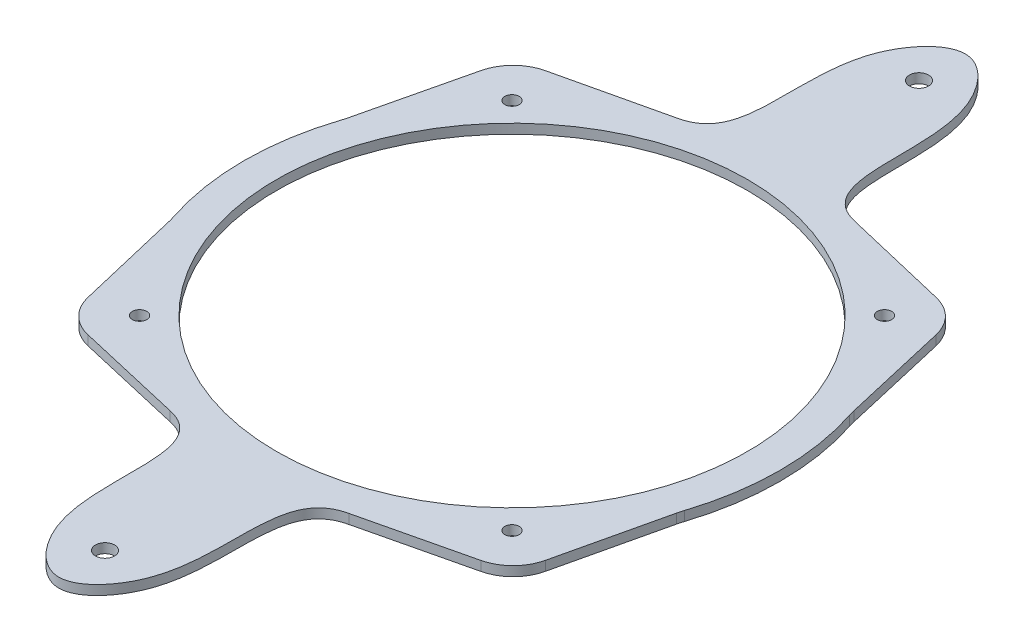
SolidWorks part; units mm, degrees
material "6061-T6 (SS)"
ref_plane "Front Plane" through (0, 0, 0) normal (0, 0, 1) x (1, 0, 0)
ref_plane "Top Plane" through (0, 0, 0) normal (0, 1, 0) x (1, 0, 0)
ref_plane "Right Plane" through (0, 0, 0) normal (1, 0, 0) x (0, 0, -1)
sketch "Sketch1" plane through (0, 0, 0) normal (0, 1, 0) x (1, 0, 0)
  line L0 (49.872, -261.8935) -> (473.872, -261.8935) construction
  line L1 (17.8971, 48.9297) -> (40.1493, 43.6512) construction
  line L2 (43.8664, 39.9141) -> (49.0252, 17.6338) construction
  line L3 (48.9297, -17.8971) -> (43.6512, -40.1493) construction
  line L4 (39.9141, -43.8664) -> (17.6338, -49.0252) construction
  line L5 (-17.8971, -48.9297) -> (-40.1493, -43.6512) construction
  line L6 (-43.8664, -39.9141) -> (-49.0252, -17.6338) construction
  line L7 (-48.9297, 17.8971) -> (-43.6512, 40.1493) construction
  line L8 (-39.9141, 43.8664) -> (-17.6338, 49.0252) construction
  line L9 (-40.8164, 47.7633) -> (-18.5361, 52.9221)
  line L10 (18.8203, 52.8217) -> (41.0725, 47.5432)
  line L11 (47.7633, 40.8164) -> (52.9221, 18.5361)
  line L12 (-38.8907, 38.8907) -> (38.8907, 38.8907) construction
  line L13 (-38.8907, 38.8907) -> (-38.8907, -38.8907) construction
  line L14 (-38.8907, -38.8907) -> (38.8907, -38.8907) construction
  line L15 (38.8907, 38.8907) -> (38.8907, -38.8907) construction
  line L20 (-52.8217, 18.8203) -> (-47.5432, 41.0725)
  line L21 (0, 38.8907) -> (0, -38.8907) construction
  line L22 (-38.8907, 0) -> (38.8907, 0) construction
  line L23 (0, 38.8907) -> (0, 94.647) construction
  line L24 (-9.2568, 85.9478) -> (0, 85.9478) construction
  line L25 (0, 85.9478) -> (9.2568, 85.9478) construction
  line L26 (-38.8907, 0) -> (-56, 0) construction
  line L27 (38.8907, 0) -> (56, 0) construction
  line L28 (-47.7633, -40.8164) -> (-52.9221, -18.5361) construction
  line L29 (-18.8203, -52.8217) -> (-41.0725, -47.5432) construction
  line L30 (40.8164, -47.7633) -> (18.5361, -52.9221) construction
  line L31 (52.8217, -18.8203) -> (47.5432, -41.0725) construction
  line L32 (-52.8217, -18.8203) -> (-47.5432, -41.0725)
  line L33 (-40.8164, -47.7633) -> (-18.5361, -52.9221)
  line L34 (18.8203, -52.8217) -> (41.0725, -47.5432)
  line L35 (47.7633, -40.8164) -> (52.9221, -18.5361)
  line L36 (0, -38.8907) -> (0, -94.647) construction
  arc A1 (-17.6338, 49.0252) -> (-15.9939, 49.4792) centre (-22.1454, 68.5097) ccw construction
  arc A2 (0.1397, 51.9998) -> (-15.9939, 49.4792) centre (0, 0) ccw construction
  arc A3 (16.2596, 49.3926) -> (0.1397, 51.9998) centre (0, 0) ccw construction
  arc A4 (16.2596, 49.3926) -> (17.8971, 48.9297) centre (22.5132, 68.3897) ccw construction
  arc A5 (43.8664, 39.9141) -> (40.1493, 43.6512) centre (38.9952, 38.7862) ccw construction
  arc A6 (49.0252, 17.6338) -> (49.4792, 15.9939) centre (68.5097, 22.1454) ccw construction
  arc A7 (49.3926, -16.2596) -> (49.4792, 15.9939) centre (0, 0) ccw construction
  arc A8 (49.3926, -16.2596) -> (48.9297, -17.8971) centre (68.3897, -22.5132) ccw construction
  arc A9 (39.9141, -43.8664) -> (43.6512, -40.1493) centre (38.7862, -38.9952) ccw construction
  arc A10 (17.6338, -49.0252) -> (15.9939, -49.4792) centre (22.1454, -68.5097) ccw construction
  arc A11 (-16.2596, -49.3926) -> (15.9939, -49.4792) centre (0, 0) ccw construction
  arc A12 (-16.2596, -49.3926) -> (-17.8971, -48.9297) centre (-22.5132, -68.3897) ccw construction
  arc A13 (-43.8664, -39.9141) -> (-40.1493, -43.6512) centre (-38.9952, -38.7862) ccw construction
  arc A14 (-49.0252, -17.6338) -> (-49.4792, -15.9939) centre (-68.5097, -22.1454) ccw construction
  arc A15 (-49.3926, 16.2596) -> (-49.4792, -15.9939) centre (0, 0) ccw construction
  arc A16 (-49.3926, 16.2596) -> (-48.9297, 17.8971) centre (-68.3897, 22.5132) ccw construction
  arc A17 (-39.9141, 43.8664) -> (-43.6512, 40.1493) centre (-38.7862, 38.9952) ccw construction
  circle A18 centre (-38.8907, 38.8907) radius 1.5
  circle A19 centre (38.8907, 38.8907) radius 1.5
  circle A20 centre (38.8907, -38.8907) radius 1.5
  circle A21 centre (-38.8907, -38.8907) radius 1.5
  arc A30 (47.7633, 40.8164) -> (41.0725, 47.5432) centre (38.9952, 38.7862) ccw
  arc A31 (52.9221, 18.5361) -> (53.2853, 17.2242) centre (68.5097, 22.1454) ccw
  arc A32 (53.2853, -17.2242) -> (53.2853, 17.2242) centre (0, 0) ccw
  arc A40 (-53.192, 17.5103) -> (-53.192, -17.5103) centre (0, 0) ccw
  arc A41 (-53.192, 17.5103) -> (-52.8217, 18.8203) centre (-68.3897, 22.5132) ccw
  arc A42 (-40.8164, 47.7633) -> (-47.5432, 41.0725) centre (-38.7862, 38.9952) ccw
  circle A43 centre (0, 0) radius 49.2
  arc A44 (-53.192, 17.5103) -> (-53.2853, -17.2242) centre (0, 0) ccw construction
  arc A45 (-52.9221, -18.5361) -> (-53.2853, -17.2242) centre (-68.5097, -22.1454) ccw construction
  arc A46 (-47.7633, -40.8164) -> (-41.0725, -47.5432) centre (-38.9952, -38.7862) ccw construction
  arc A47 (-17.5103, -53.192) -> (17.2242, -53.2853) centre (0, 0) ccw construction
  arc A48 (-17.5103, -53.192) -> (-18.8203, -52.8217) centre (-22.5132, -68.3897) ccw construction
  arc A49 (18.5361, -52.9221) -> (17.2242, -53.2853) centre (22.1454, -68.5097) ccw construction
  arc A50 (40.8164, -47.7633) -> (47.5432, -41.0725) centre (38.7862, -38.9952) ccw construction
  arc A51 (53.192, -17.5103) -> (52.8217, -18.8203) centre (68.3897, -22.5132) ccw construction
  arc A52 (53.192, -17.5103) -> (53.2853, 17.2242) centre (0, 0) ccw construction
  arc A53 (0.1505, 55.9998) -> (-17.2242, 53.2853) centre (0, 0) ccw construction
  arc A54 (17.5103, 53.192) -> (0.1505, 55.9998) centre (0, 0) ccw construction
  arc A55 (-18.5361, 52.9221) -> (-17.2242, 53.2853) centre (-22.1454, 68.5097) ccw construction
  arc A56 (17.5103, 53.192) -> (18.8203, 52.8217) centre (22.5132, 68.3897) ccw construction
  arc A57 (-53.192, -17.5103) -> (-52.8217, -18.8203) centre (-68.3897, -22.5132) cw
  arc A58 (-40.8164, -47.7633) -> (-47.5432, -41.0725) centre (-38.7862, -38.9952) cw
  arc A59 (47.7633, -40.8164) -> (41.0725, -47.5432) centre (38.9952, -38.7862) cw
  arc A60 (52.9221, -18.5361) -> (53.2853, -17.2242) centre (68.5097, -22.1454) cw
  circle A61 centre (0, 85) radius 2
  circle A62 centre (0, -85) radius 2
  spline S0 degree 3 poles (-18.5361, 52.9221) (-6.5366, 55.4554) (-17.4506, 79.5033) (0.008, 98.6838) (17.4365, 79.4328) (6.7962, 55.4361) (18.8203, 52.8217) knots 0 0 0 0 0.36619 0.499165 0.632141 1 1 1 1
  spline S1 degree 3 poles (-18.5361, -52.9221) (-6.5366, -55.4554) (-17.4506, -79.5033) (0.008, -98.6838) (17.4365, -79.4328) (6.7962, -55.4361) (18.8203, -52.8217) knots 0 0 0 0 0.36619 0.499165 0.632141 1 1 1 1
  point P102 (0, 90.6068)
  point P135 (0, 81.9698)
  point P136 (0, 94.647)
  point P137 (9.2568, 85.9478)
  dimension "D1" = 3
  dimension "D2" = 4
  dimension "D3" = 98.4
  dimension "D4" = 4
  dimension "D5" = 170
extrude "Boss-Extrude1" add sketch "Sketch1" along normal blind 2
